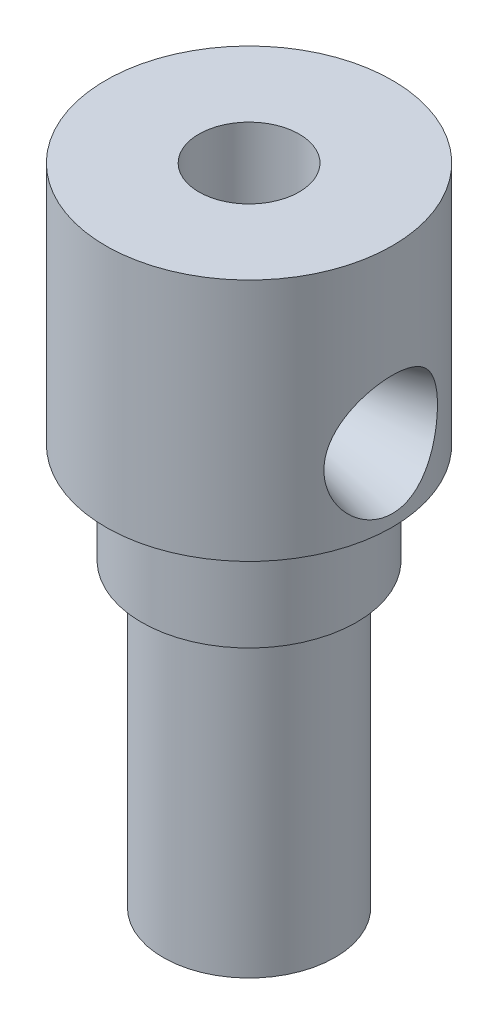
SolidWorks part; units mm, degrees
ref_plane "Front Plane" through (0, 0, 0) normal (0, 0, 1) x (1, 0, 0)
ref_plane "Top Plane" through (0, 0, 0) normal (0, 1, 0) x (1, 0, 0)
ref_plane "Right Plane" through (0, 0, 0) normal (1, 0, 0) x (0, 0, -1)
sketch "Sketch1" plane through (0, 0, 0) normal (0, 0, 1) x (1, 0, 0)
  line L0 (3.5, 0) -> (6, 0)
  line L1 (6, 0) -> (6, 21)
  line L2 (6, 21) -> (7.5, 21)
  line L3 (7.5, 21) -> (7.5, 28)
  line L4 (7.5, 28) -> (10, 28)
  line L5 (10, 28) -> (10, 45)
  line L6 (10, 45) -> (3.5, 45)
  line L7 (3.5, 45) -> (3.5, 0)
  line L8 (0, -1000) -> (0, 49000) construction
  dimension "D1" = 6
  dimension "D2" = 7.5
  dimension "D3" = 10
  dimension "D4" = 45
  dimension "D5" = 17
  dimension "D6" = 7
  dimension "D7" = 3.5
revolve "Revolve1" add sketch "Sketch1" angle 360 about L8
sketch "Sketch2" plane through (0, 0, 0) normal (1, 0, 0) x (0, 0, -1)
  line L0 (0, 40) -> (0, 33) construction
  line L1 (2, 40) -> (2, 33)
  line L2 (-2, 40) -> (-2, 33)
  line L3 (3.5, 45) -> (-3.5, 45) construction
  arc A0 (2, 40) -> (-2, 40) centre (0, 40) ccw
  arc A1 (-2, 33) -> (2, 33) centre (0, 33) ccw
  point P2 (0, 36.5)
  point P7 (-0.4138, 41.3745)
  dimension "D1" = 2
  dimension "D2" = 5
  dimension "D3" = 7
extrude "Cut-Extrude2" cut sketch "Sketch2" against normal blind 10 from offset 8 contours L2 A1 L1 A0 offset against normal yes
sketch "Sketch3" plane through (-8, 0, 0) normal (-1, 0, 0) x (0, 0, 1)
  circle A0 centre (0, 33) radius 1.5
  arc A1 (-2, 33) -> (2, 33) centre (0, 33) ccw construction
  dimension "D1" = 3
extrude "Cut-Extrude3" cut sketch "Sketch3" against normal up to next
sketch "Sketch4" plane through (0, 0, 0) normal (1, 0, 0) x (0, 0, -1)
  circle A0 centre (0, 33) radius 1.5 construction
  circle A1 centre (0, 33) radius 1.5
extrude "Cut-Extrude5" cut sketch "Sketch4" along normal blind 10 draft 15 draft outward yes
